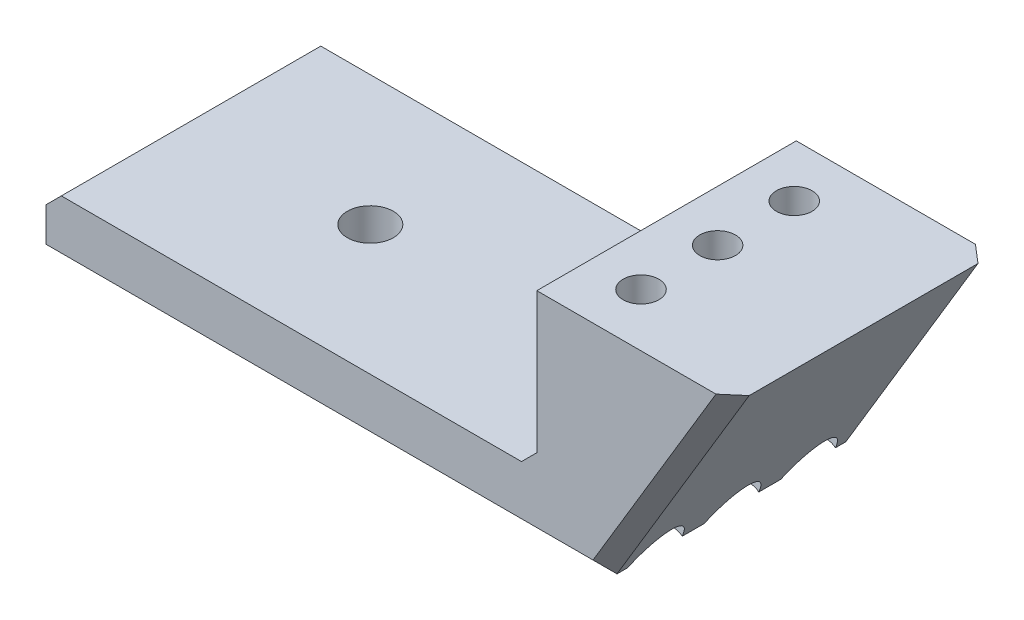
SolidWorks part; units mm, degrees
ref_plane "Front Plane" through (0, 0, 0) normal (0, 0, 1) x (1, 0, 0)
ref_plane "Top Plane" through (0, 0, 0) normal (0, 1, 0) x (1, 0, 0)
ref_plane "Right Plane" through (0, 0, 0) normal (1, 0, 0) x (0, 0, -1)
sketch "Sketch1" plane through (0, 0, 0) normal (0, 0, 1) x (1, 0, 0)
  line L0 (0, 0) -> (0, -15.24)
  line L1 (0, -15.24) -> (-48.05, -15.24)
  line L3 (6.35, -21.59) -> (-48.05, -21.59)
  line L4 (6.35, 0) -> (0, 0)
  line L5 (-48.05, -15.24) -> (-48.05, -21.59)
  line L6 (6.35, -21.59) -> (19.29, 0)
  line L7 (6.35, 0) -> (19.29, 0)
  line L9 (6.35, 0) -> (6.35, -21.59) construction
  dimension "D1" = 15.24
  dimension "D2" = 48.05
  dimension "D4" = 67.34
  dimension "D3" = 6.35
extrude "Boss-Extrude1" add sketch "Sketch1" along normal blind 25.4
sketch "Sketch4" plane through (0, -21.59, 0) normal (0, -1, 0) x (1, 0, 0)
  line L1 (-48.05, 25.4) -> (6.35, 25.4) construction
  line L2 (-48.05, 25.4) -> (-48.05, 0) construction
  point P0 (5, 20.2)
  point P1 (5, 12.7)
  point P2 (5, 5.2)
  dimension "D1" = 15
  dimension "D2" = 7.5
  dimension "D3" = 5.2
  dimension "D4" = 53.05
hole_wizard "CBORE for M5 Hex Head Bolt1" positions "3DSketch2" profile "Sketch5" counterbore size "M5" standard "ANSI Metric"
sketch3d "3DSketch2"
  point P0 (5, -21.59, 20.2)
  point P3 (5, -21.59, 12.7)
  point P6 (5, -21.59, 5.2)
sketch "Sketch5" plane through (5, -21.59, 20.2) normal (1, 0, 0) x (0, 0, -1)
  line L0 (0, 0) -> (0, 21.59)
  line L1 (0, 21.59) -> (1.75, 21.59)
  line L2 (1.75, 21.59) -> (1.75, 10)
  line L3 (1.75, 10) -> (3, 10)
  line L4 (3, 10) -> (3, 0)
  line L5 (3, 0) -> (0, 0)
  line L10 (0, 21.59) -> (-1.75, 21.59) construction
  line L11 (0, -6.35) -> (0, 107.95) construction
  dimension "Hole Dia." = 3.5
  dimension "Hole Depth" = 21.59
  dimension "C'Bore Dia." = 6
  dimension "C'Bore Depth" = 10
  dimension "Drill Angle" = 180
chamfer "Chamfer2" distance 1.5 angle 45 6 edges at (-48.05, -15.24, 12.7) (0, -15.24, 12.7) (-20.85, -21.59, 0) (12.82, -10.795, 0) (12.82, -10.795, 25.4) (-20.85, -21.59, 25.4)
sketch "Sketch7" plane through (0, -21.59, 0) normal (0, -1, 0) x (1, 0, 0)
  circle A0 centre (-29, 12.7) radius 2.25
  dimension "D1" = 4.5
extrude "Cut-Extrude1" cut sketch "Sketch7" against normal up to surface (6.35 mm away) up to face at (-24.025, -15.24, 12.7)
sketch "Sketch8" plane through (0, -11.59, 0) normal (0, -1, 0) x (1, 0, 0)
  circle A0 centre (5, 20.2) radius 1.75
  circle A1 centre (5, 12.7) radius 1.75
  circle A2 centre (5, 5.2) radius 1.75
extrude "Boss-Extrude2" add sketch "Sketch8" against normal blind 0.12
